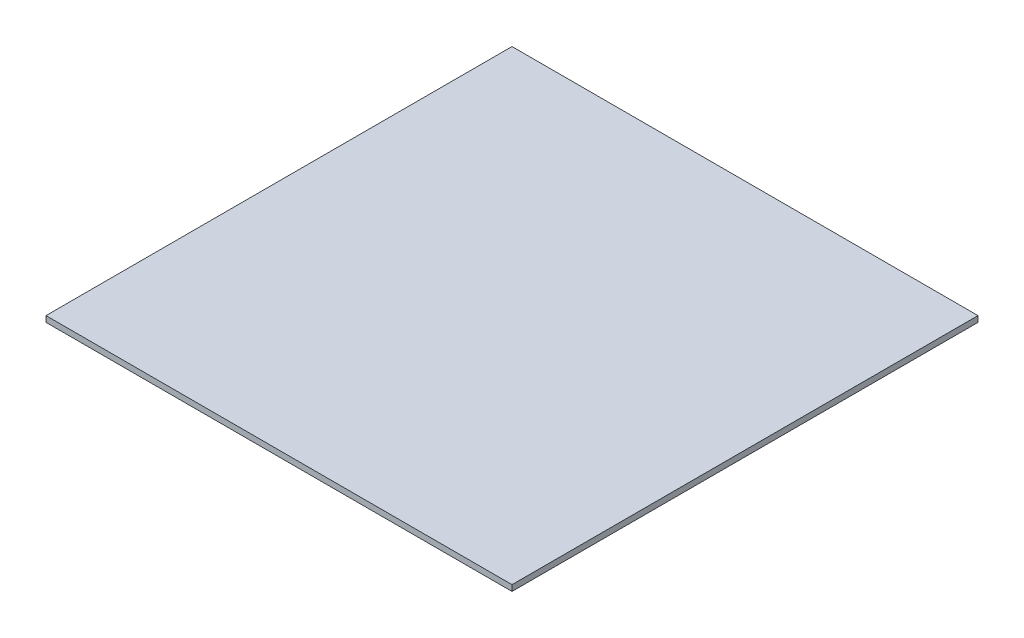
SolidWorks part; units mm, degrees
ref_plane "Front Plane" through (0, 0, 0) normal (0, 0, 1) x (1, 0, 0)
ref_plane "Top Plane" through (0, 0, 0) normal (0, 1, 0) x (1, 0, 0)
ref_plane "Right Plane" through (0, 0, 0) normal (1, 0, 0) x (0, 0, -1)
sketch "Sketch1" plane through (0, 0, 0) normal (0, 1, 0) x (1, 0, 0)
  line L1 (0, 0) -> (-473, 0)
  line L2 (0, 0) -> (0, 473)
  line L3 (0, 473) -> (-473, 473)
  line L4 (-473, 0) -> (-473, 473)
  dimension "D1" = 473
extrude "Boss-Extrude1" add sketch "Sketch1" along normal blind 6
